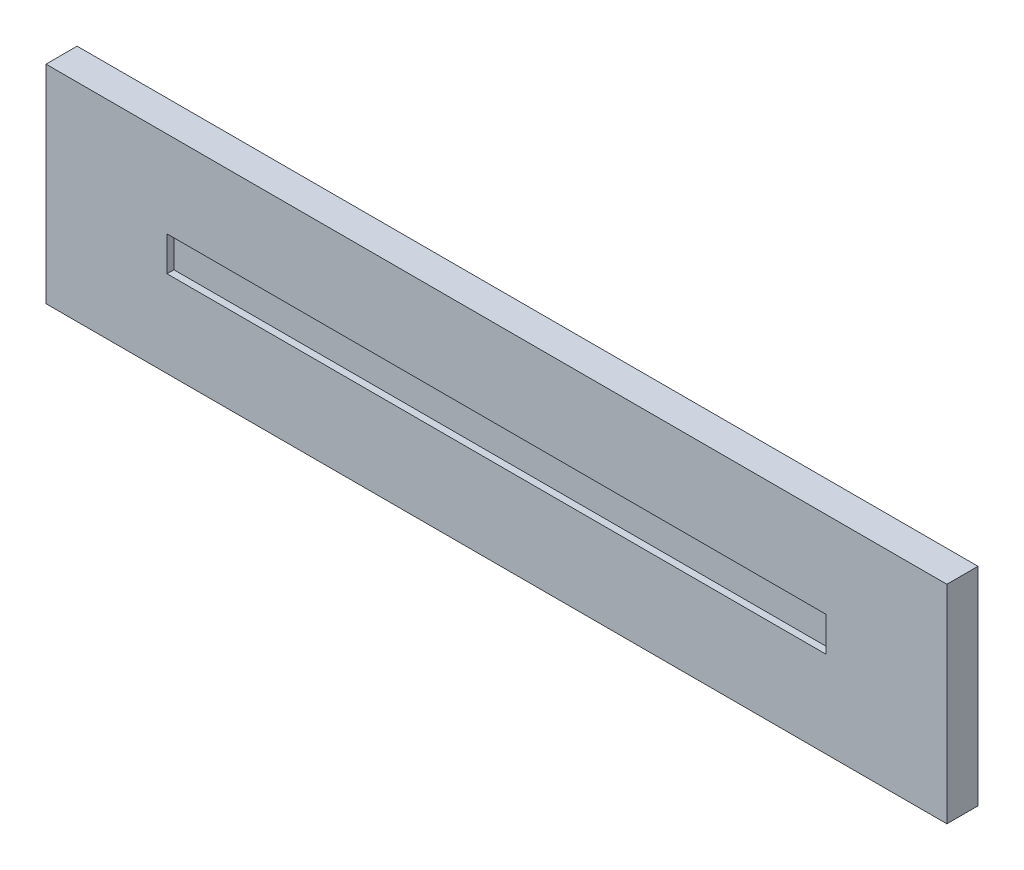
SolidWorks part; units mm, degrees
material "Pine"
ref_plane "Front Plane" through (0, 0, 0) normal (0, 0, 1) x (1, 0, 0)
ref_plane "Top Plane" through (0, 0, 0) normal (0, 1, 0) x (1, 0, 0)
ref_plane "Right Plane" through (0, 0, 0) normal (1, 0, 0) x (0, 0, -1)
sketch "Sketch1" plane through (0, 0, 0) normal (0, 0, 1) x (1, 0, 0)
  line L1 (-260.5, 60) -> (260.5, 60)
  line L2 (-260.5, 60) -> (-260.5, -60)
  line L3 (-260.5, -60) -> (260.5, -60)
  line L4 (260.5, 60) -> (260.5, -60)
  line L5 (-260.5, 60) -> (260.5, -60) construction
  line L6 (-260.5, -60) -> (260.5, 60) construction
  point P0 (0, 0)
  dimension "D1" = 120
  dimension "D2" = 521
extrude "Boss-Extrude1" add sketch "Sketch1" along normal blind 18
sketch "Sketch2" plane through (0, 0, 18) normal (0, 0, 1) x (1, 0, 0)
  line L0 (-260.5, 60) -> (-260.5, -60) construction
  line L1 (-190.5, -10) -> (190.5, -10)
  line L2 (-190.5, -10) -> (-190.5, 10)
  line L3 (-190.5, 10) -> (190.5, 10)
  line L4 (190.5, -10) -> (190.5, 10)
  line L5 (-190.5, -10) -> (190.5, 10) construction
  line L6 (-190.5, 10) -> (190.5, -10) construction
  line L7 (260.5, 60) -> (-260.5, 60) construction
  point P0 (0, 0)
  dimension "D1" = 70
  dimension "D2" = 70
extrude "Cut-Extrude1" cut sketch "Sketch2" against normal blind 4
